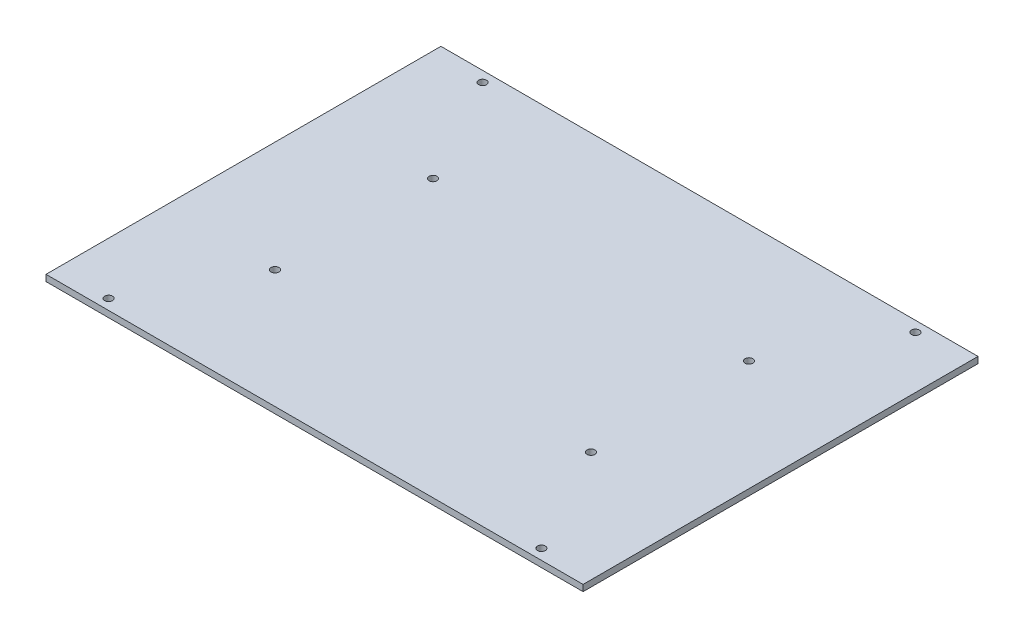
SolidWorks part; units mm, degrees
ref_plane "Plan de face" through (0, 0, 0) normal (0, 0, 1) x (1, 0, 0)
ref_plane "Plan de dessus" through (0, 0, 0) normal (0, 1, 0) x (1, 0, 0)
ref_plane "Plan de droite" through (0, 0, 0) normal (1, 0, 0) x (0, 0, -1)
sketch "Esquisse1" plane through (0, 0, 0) normal (0, 1, 0) x (1, 0, 0)
  line L0 (-85, -62.5) -> (85, 62.5) construction
  line L1 (-85, 62.5) -> (85, 62.5)
  line L2 (-85, 62.5) -> (-85, -62.5)
  line L3 (-85, -62.5) -> (85, -62.5)
  line L4 (85, 62.5) -> (85, -62.5)
  dimension "D1" = 170
  dimension "D2" = 125
extrude "Boss.-Extru.1" add sketch "Esquisse1" along normal blind 2
hole_wizard "Trou pour taraudage pour trou taraudé M3x0.51" positions "Esquisse2" profile "Esquisse3" hole size "M3x0.5" standard "Ansi Metric" end condition through all
sketch "Esquisse2" plane through (0, 2, 0) normal (0, 1, 0) x (1, 0, 0)
  line L0 (85, 62.5) -> (-85, -62.5) construction
  line L1 (-50, -25) -> (-85, -25) construction
  line L2 (-85, 62.5) -> (-85, -62.5) construction
  line L5 (50, 25) -> (85, 25) construction
  line L6 (85, -62.5) -> (85, 62.5) construction
  line L8 (51.0954, 25) -> (51.0954, 62.5) construction
  line L9 (85, 62.5) -> (-85, 62.5) construction
  line L11 (-50, -25) -> (-50, -62.5) construction
  line L12 (-85, -62.5) -> (85, -62.5) construction
  line L17 (68.5, 59.2) -> (68.5, 62.5) construction
  line L19 (-68.5, -62.5) -> (-68.5, -59.2) construction
  line L20 (68.5, 59.2) -> (85, 59.2) construction
  line L22 (-68.5, -59.2) -> (-85, -59.2) construction
  point P0 (-50, 25)
  point P2 (50, 25)
  point P4 (50, -25)
  point P6 (-50, -25)
  point P51 (68.5, 59.2)
  point P53 (-68.5, -59.2)
  point P55 (-68.5, 59.2)
  point P57 (68.5, -59.2)
  dimension "D1" = 100
  dimension "D2" = 50
  dimension "D3" = 3.3
  dimension "D4" = 16.5
sketch "Esquisse3" plane through (-50, 2, -25) normal (1, 0, 0) x (0, 0, 1)
  line L0 (0, 0) -> (0, 2)
  line L1 (0, 2) -> (1.25, 2)
  line L2 (1.25, 2) -> (1.25, 0)
  line L5 (1.25, 0) -> (0, 0)
  line L11 (0, -6.35) -> (0, 107.95) construction
  dimension "Diamètre du perçage jusqu'au prochain" = 2.5
  dimension "Profondeur du perçage jusqu'au prochain" = 2
